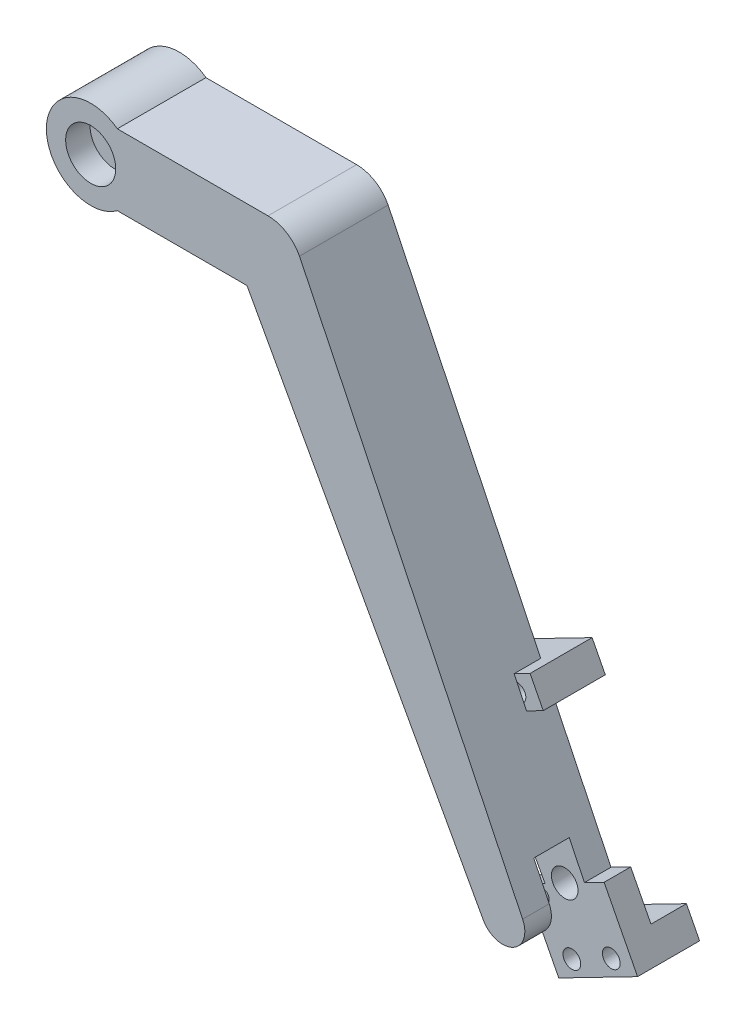
SolidWorks part; units mm, degrees
ref_plane "前视基准面" through (0, 0, 0) normal (0, 0, 1) x (1, 0, 0)
ref_plane "上视基准面" through (0, 0, 0) normal (0, 1, 0) x (1, 0, 0)
ref_plane "右视基准面" through (0, 0, 0) normal (1, 0, 0) x (0, 0, -1)
other "Configuration Table"
sketch "草图1" plane through (0, 0, 0) normal (0, 0, 1) x (1, 0, 0)
  line L0 (0, 0) -> (40, 0) construction
  line L2 (0, 0) -> (40, 0) construction
  line L3 (6, 8) -> (40, 8)
  line L4 (6, -8) -> (35.264, -8)
  line L5 (40, 0) -> (93.0095, -103) construction
  line L6 (40, 0) -> (47.1132, 3.6609) construction
  line L7 (40, 0) -> (32.8868, -3.6609) construction
  line L8 (88.5638, -105.288) -> (97.4553, -100.712) construction
  line L9 (47.1132, 3.6609) -> (97.4553, -100.712)
  line L11 (35.264, -8) -> (88.5638, -105.288)
  arc A0 (6, 8) -> (6, -8) centre (0, 0) ccw
  arc A2 (47.1132, 3.6609) -> (40, 8) centre (40, 0) ccw
  arc A5 (47.1132, 3.6609) -> (40, 8) centre (40, 0) ccw
  arc A6 (97.4553, -100.712) -> (88.5638, -105.288) centre (92.9503, -102.8849) cw
  point P6 (20, 0)
  dimension "D1" = 20
  dimension "D2" = 103
  dimension "D3" = 40
extrude "凸台-拉伸1" add sketch "草图1" along normal blind 20 contours L11 A6 L9 A2 L3 A0 L4
sketch "草图2" plane through (0, 0, 20) normal (0, 0, 1) x (1, 0, 0)
  circle A0 centre (0, 0) radius 5.65
  dimension "D1" = 11.3
extrude "切除-拉伸1" cut sketch "草图2" against normal blind 5.5
sketch "草图4" plane through (0, 0, 0) normal (0, 0, -1) x (-1, 0, 0)
  line L0 (-97.4553, -100.712) -> (-88.5638, -105.288) construction
  line L1 (-97.4553, -100.712) -> (-93.9786, -93.5039)
  line L2 (-47.1132, 3.6609) -> (-97.4553, -100.712) construction
  line L3 (-93.9786, -93.5039) -> (-84.7187, -98.2696)
  line L4 (-35.264, -8) -> (-88.5638, -105.288) construction
  line L5 (-84.7187, -98.2696) -> (-88.5638, -105.288)
  arc A0 (-97.4553, -100.712) -> (-88.5638, -105.288) centre (-93.0095, -103) ccw
  dimension "D2" = 8
extrude "切除-拉伸4" cut sketch "草图4" against normal blind 8 from offset 6 offset against normal yes
sketch "草图5" plane through (0, 0, 6) normal (0, 0, 1) x (1, 0, 0)
  circle A0 centre (92.9503, -102.8849) radius 1.5
  dimension "D1" = 3
extrude "凸台-拉伸2" add sketch "草图5" along normal blind 3 from offset 5
sketch "草图7" plane through (0, 0, 0) normal (0, 0, -1) x (-1, 0, 0)
  circle A0 centre (-92.9503, -102.8849) radius 3
  dimension "D1" = 6
extrude "切除-拉伸5" cut sketch "草图7" against normal up to next
sketch "草图8" plane through (0, 0, 0) normal (0, 0, -1) x (-1, 0, 0)
  line L0 (-92.9503, -102.8849) -> (-81.6188, -80.8672) construction
  line L1 (-35.264, -8) -> (-88.5638, -105.288) construction
  line L2 (-47.1132, 3.6609) -> (-97.4553, -100.712) construction
  line L11 (-95.6177, -101.512) -> (-101.8418, -98.3088)
  line L12 (-101.8418, -98.3088) -> (-109.3923, -112.9798)
  line L13 (-109.3923, -112.9798) -> (-91.6093, -122.132)
  line L14 (-91.6093, -122.132) -> (-84.0587, -107.4609)
  line L15 (-84.0587, -107.4609) -> (-90.2828, -104.2577)
  arc A0 (-95.6177, -101.512) -> (-90.2828, -104.2577) centre (-92.9503, -102.8849) ccw
  dimension "D1" = 20
  dimension "D2" = 16.5
extrude "凸台-拉伸3" add sketch "草图8" against normal blind 6
sketch "草图9" plane through (0, 0, 0) normal (0, 0, -1) x (-1, 0, 0)
  line L0 (-106.4179, -107.2003) -> (-88.6348, -116.3525)
  line L1 (-101.8418, -98.3088) -> (-109.3923, -112.9798) construction
  line L2 (-91.6093, -122.132) -> (-84.0587, -107.4609) construction
  line L3 (-109.3923, -112.9798) -> (-91.6093, -122.132) construction
  line L4 (-106.4179, -107.2003) -> (-109.3923, -112.9798)
  line L5 (-109.3923, -112.9798) -> (-91.6093, -122.132)
  line L6 (-91.6093, -122.132) -> (-88.6348, -116.3525)
  dimension "D1" = 6.5
extrude "凸台-拉伸4" add sketch "草图9" along normal blind 8
sketch "草图10" plane through (0, 0, 0) normal (0, 0, -1) x (-1, 0, 0)
  line L0 (-97.5264, -111.7764) -> (-75.0035, -68.0134) construction
  line L1 (-88.6348, -116.3525) -> (-106.4179, -107.2003) construction
  line L2 (-88.1136, -71.6342) -> (-70.3305, -80.7863)
  line L3 (-70.3305, -80.7863) -> (-67.356, -75.0068)
  line L4 (-67.356, -75.0068) -> (-85.1391, -65.8547)
  line L5 (-88.1136, -71.6342) -> (-85.1391, -65.8547)
  point P9 (-76.2476, -70.4307)
  point P10 (-79.222, -76.2102)
  dimension "D1" = 20
  dimension "D2" = 6.5
  dimension "D3" = 40
extrude "凸台-拉伸5" add sketch "草图10" along normal blind 8
sketch "草图11" plane through (0, 0, 0) normal (0, 0, 1) x (1, 0, 0)
  line L0 (81.5368, -67.7086) -> (84.3616, -73.5651)
  line L1 (84.3616, -73.5651) -> (81.5368, -67.7086) construction
  line L2 (47.1132, 3.6609) -> (97.4553, -100.712) construction
  line L3 (84.3616, -73.5651) -> (88.1136, -71.6342)
  line L4 (88.1136, -71.6342) -> (85.1391, -65.8547)
  line L5 (85.1391, -65.8547) -> (81.5368, -67.7086)
  line L6 (67.356, -75.0068) -> (70.3305, -80.7863)
  line L7 (70.3305, -80.7863) -> (74.0825, -78.8553)
  line L8 (74.0825, -78.8553) -> (70.9583, -73.1529)
  line L9 (70.9583, -73.1529) -> (67.356, -75.0068)
extrude "凸台-拉伸6" add sketch "草图11" along normal blind 6
sketch "草图12" plane through (0, 0, -8) normal (0, 0, -1) x (-1, 0, 0)
  line L0 (-100.5008, -117.5559) -> (-76.2476, -70.4307) construction
  line L1 (-109.3923, -112.9798) -> (-91.6093, -122.132) construction
  line L2 (-67.356, -75.0068) -> (-85.1391, -65.8547) construction
  line L3 (-88.3742, -93.9933) -> (-83.6952, -96.4014) construction
  line L4 (-74.0825, -78.8553) -> (-88.5015, -105.1744) construction
  line L5 (-83.6952, -96.4014) -> (-93.0532, -91.5852) construction
  line L6 (-84.3616, -73.5651) -> (-97.399, -100.5953) construction
  line L7 (-107.9051, -110.0901) -> (-90.122, -119.2422) construction
  line L8 (-106.4179, -107.2003) -> (-109.3923, -112.9798) construction
  line L9 (-91.6093, -122.132) -> (-88.6348, -116.3525) construction
  circle A0 centre (-103.4593, -112.3781) radius 2
  circle A1 centre (-94.5678, -116.9542) radius 2
  circle A2 centre (-73.289, -75.6085) radius 2
  circle A3 centre (-82.1806, -71.0325) radius 2
  dimension "D1" = 4
  dimension "D2" = 5
extrude "切除-拉伸7" cut sketch "草图12" against normal up to surface (14 mm away) up to face at (93.9375, -104.8031, 6)
